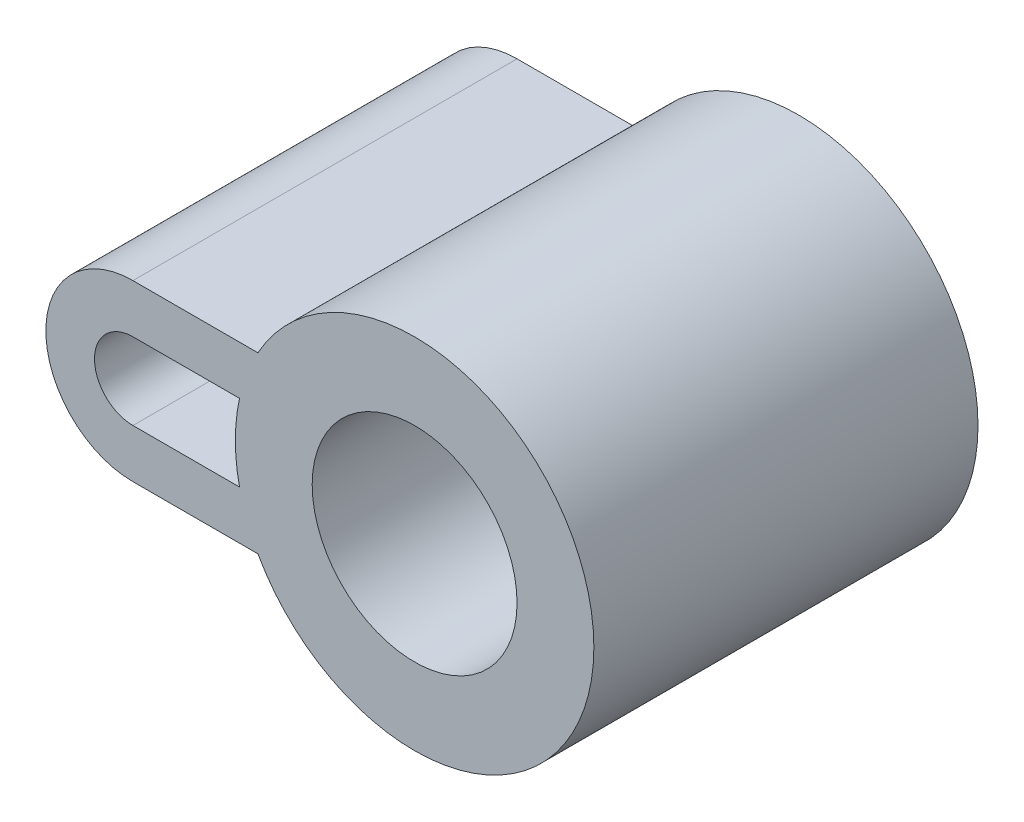
SolidWorks part; units mm, degrees
ref_plane "Front Plane" through (0, 0, 0) normal (0, 0, 1) x (1, 0, 0)
ref_plane "Top Plane" through (0, 0, 0) normal (0, 1, 0) x (1, 0, 0)
ref_plane "Right Plane" through (0, 0, 0) normal (1, 0, 0) x (0, 0, -1)
sketch "Sketch1" plane through (0, 0, 0) normal (0, 0, 1) x (1, 0, 0)
  line L2 (-55, 17) -> (-30.5941, 17) construction
  line L3 (-55, -17) -> (-30.5941, -17) construction
  line L4 (-30.5941, 17) -> (-55, 17)
  line L6 (-55, -17) -> (-30.5941, -17)
  line L7 (-55, -7.5) -> (-34.187, -7.5)
  line L8 (-55, 7.5) -> (-34.187, 7.5)
  circle A0 centre (0, 0) radius 35
  circle A1 centre (0, 0) radius 20
  arc A2 (-55, 17) -> (-55, -17) centre (-55, 0) ccw
  arc A4 (-55, 7.5) -> (-55, -7.5) centre (-55, 0) ccw
  dimension "D1" = 70
  dimension "D2" = 40
  dimension "D4" = 7.5
  dimension "D3" = 34
extrude "Boss-Extrude1" add sketch "Sketch1" along normal blind 75 contours A0 A1 | A4 L8 A0 L4 A2 L6 L7
sketch "Sketch2" plane through (0, 0, 75) normal (0, 0, 1) x (1, 0, 0)
  line L1 (0, 0) -> (0, -50000) construction
  line L2 (-22.5, -26.8095) -> (-22.5, -65.874)
  line L4 (-7.5, -75.874) -> (-7.5, -34.187)
  line L5 (7.5, -75.874) -> (7.5, -34.187)
  line L6 (-22.5, -65.874) -> (-22.5, -75.874)
  line L7 (22.5, -26.8095) -> (22.5, -65.874)
  line L8 (-22.5, -75.874) -> (-7.5, -75.874)
  line L10 (7.5, -75.874) -> (22.5, -75.874)
  line L11 (22.5, -75.874) -> (22.5, -65.874)
  arc A0 (-30.5941, -17) -> (-30.5941, 17) centre (0, 0) ccw construction
  point P13 (-22.5, -75.874)
  dimension "D1" = 7.5
